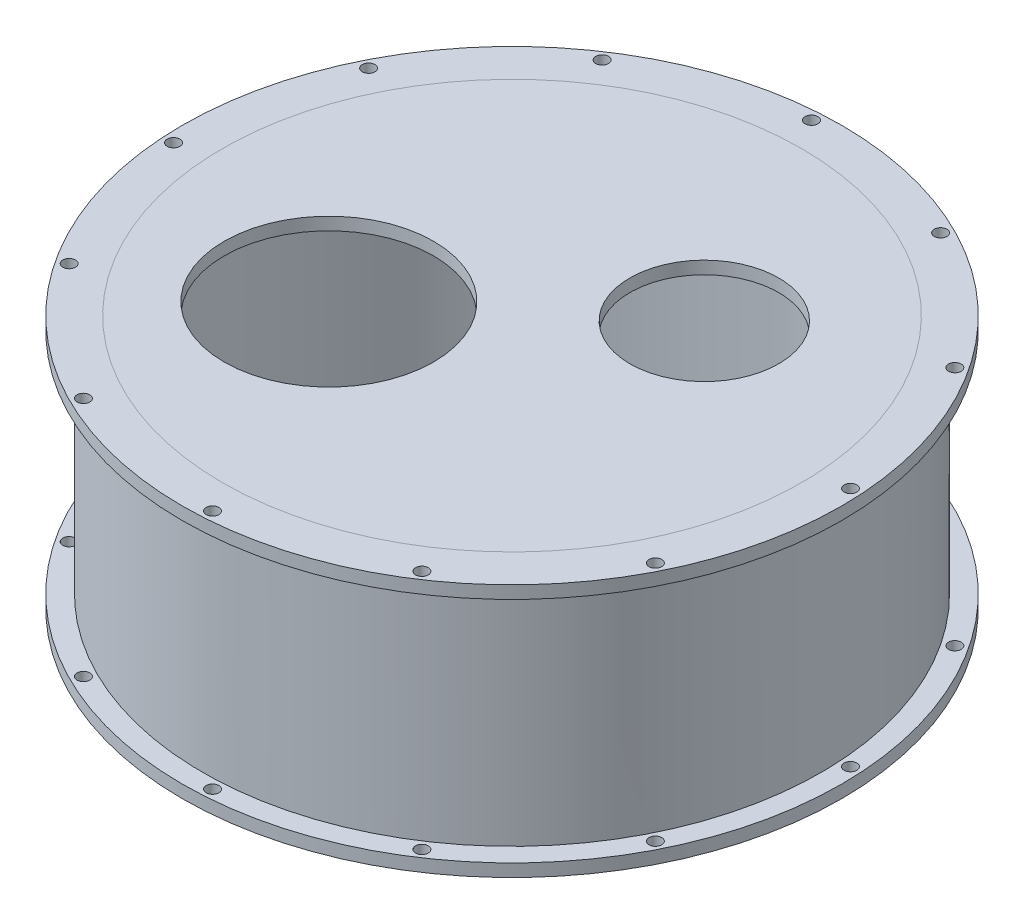
SolidWorks part; units mm, degrees
ref_plane "Front Plane" through (0, 0, 0) normal (0, 0, 1) x (1, 0, 0)
ref_plane "Top Plane" through (0, 0, 0) normal (0, 1, 0) x (1, 0, 0)
ref_plane "Right Plane" through (0, 0, 0) normal (1, 0, 0) x (0, 0, -1)
sketch "Sketch1" plane through (0, 0, 0) normal (0, 1, 0) x (1, 0, 0)
  circle A0 centre (0, 0) radius 155
  circle A3 centre (0, 0) radius 145
  dimension "D1" = 310
  dimension "D2" = 290
extrude "Boss-Extrude1" add sketch "Sketch1" along normal blind 63.5
ref_plane "Plane1" through (0, 0, 0) normal (0, -1, 0) x (-1, 0, 0)
sketch "Sketch2" plane through (0, 0, 0) normal (0, -1, 0) x (1, 0, 0)
  circle A0 centre (0, 0) radius 155 construction
  circle A1 centre (0, 0) radius 155
  circle A2 centre (0, 0) radius 165.16
  dimension "D1" = 10.16
extrude "Boss-Extrude2" add sketch "Sketch2" against normal blind 6.35
ref_plane "Plane2" through (0, 63.5, 0) normal (0, 1, 0) x (1, 0, 0)
mirror "Mirror2" about plane through (0, 63.5, 0) normal (0, 1, 0) of "Boss-Extrude2", "Boss-Extrude1"
sketch "Sketch3" plane through (0, 127, 0) normal (0, 1, 0) x (1, 0, 0)
  circle A0 centre (0, 0) radius 145 construction
  circle A1 centre (0, 0) radius 145
  circle A2 centre (50.4368, 45.8953) radius 37.2774
  circle A3 centre (-51.9358, -39.8005) radius 52.4437
extrude "Boss-Extrude4" add sketch "Sketch3" against normal blind 6.35 separate body contours A1 | A3 | A2
sketch "Sketch7" plane through (0, 127, 0) normal (0, 1, 0) x (1, 0, 0)
  line L0 (0, 0) -> (10.077, -164.8523) construction
  line L1 (10.077, -164.8523) -> (9.4571, -154.7112) construction
  circle A0 centre (0, 0) radius 155 construction
  circle A1 centre (0, 0) radius 165.16
  circle A2 centre (0, 0) radius 165.16
  circle A3 centre (0, 0) radius 155
  point P6 (9.7671, -159.7818)
  dimension "D1" = 0
hole_wizard "1/4 (0.25) Diameter Hole2" positions "3DSketch1" profile "Sketch10" hole size "1/4" standard "ANSI Inch"
sketch3d "3DSketch1"
  point P0 (9.7671, 127, 159.7818)
sketch "Sketch10" plane through (9.7671, 127, 159.7818) normal (1, 0, 0) x (0, 0, 1)
  line L0 (0, 0) -> (0, 8.2577)
  line L1 (0, 8.2577) -> (3.175, 6.35)
  line L2 (3.175, 6.35) -> (3.175, 0)
  line L5 (3.175, 0) -> (0, 0)
  line L10 (0, 8.2577) -> (-3.175, 6.35) construction
  line L11 (0, -6.35) -> (0, 107.95) construction
  dimension "Hole Dia." = 6.35
  dimension "Hole Depth" = 6.35
  dimension "Drill Angle" = 118
mirror "Mirror6" about plane through (0, 63.5, 0) normal (0, 1, 0) of "1/4 (0.25) Diameter Hole2"
pattern_circular "CirPattern2" count 12 over 360 about axis through (0, 0, 0) along (0, 1, 0) of "1/4 (0.25) Diameter Hole2", "Mirror6"
